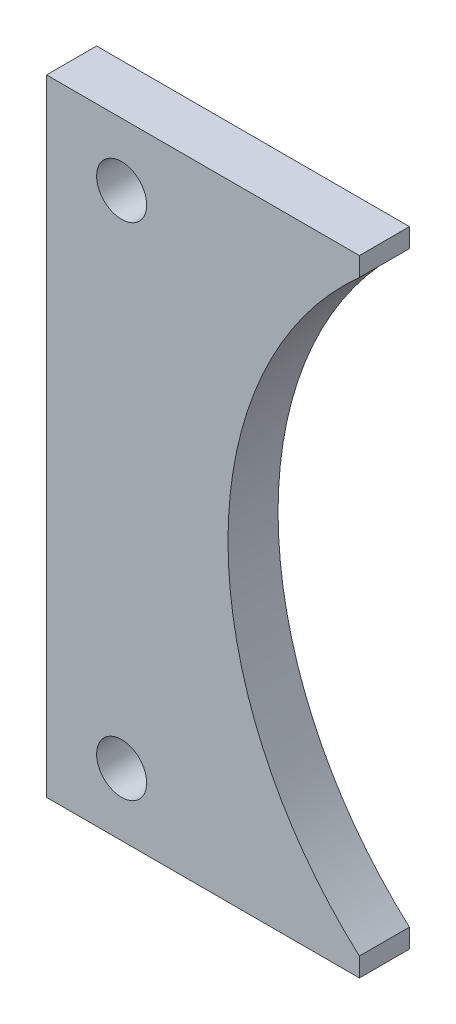
SolidWorks part; units mm, degrees
ref_plane "前视基准面" through (0, 0, 0) normal (0, 0, 1) x (1, 0, 0)
ref_plane "上视基准面" through (0, 0, 0) normal (0, 1, 0) x (1, 0, 0)
ref_plane "右视基准面" through (0, 0, 0) normal (1, 0, 0) x (0, 0, -1)
sketch "草图1" plane through (0, 0, 0) normal (0, 0, 1) x (1, 0, 0)
  line L0 (0, 0) -> (-40, 0) construction
  line L1 (-40, 0) -> (-40, -20) construction
  line L2 (-40, 0) -> (-40, 20) construction
  line L3 (-21, 23.4787) -> (-21, 25)
  line L4 (-46, 25) -> (-21, 25)
  line L5 (-46, 25) -> (-46, -25)
  line L6 (-46, -25) -> (-21, -25)
  line L7 (-21, 25) -> (-21, -25) construction
  line L8 (-21, -23.4787) -> (-21, -25)
  circle A0 centre (0, 0) radius 31.5 construction
  circle A1 centre (-40, 20) radius 2
  circle A2 centre (-40, -20) radius 2
  arc A3 (-21, -23.4787) -> (-21, 23.4787) centre (0, 0) cw
  point P17 (-26.9803, 0)
  point P18 (-35.1839, 21.4428)
  dimension "D1" = 50
  dimension "D4" = 20
  dimension "D7" = 4
  dimension "D8" = 4
  dimension "D9" = 40
  dimension "D10" = 63
  dimension "D2" = 25
  dimension "D3" = 25
  dimension "D5" = 20
  dimension "D6" = 6
extrude "凸台-拉伸1" add sketch "草图1" along normal blind 4
